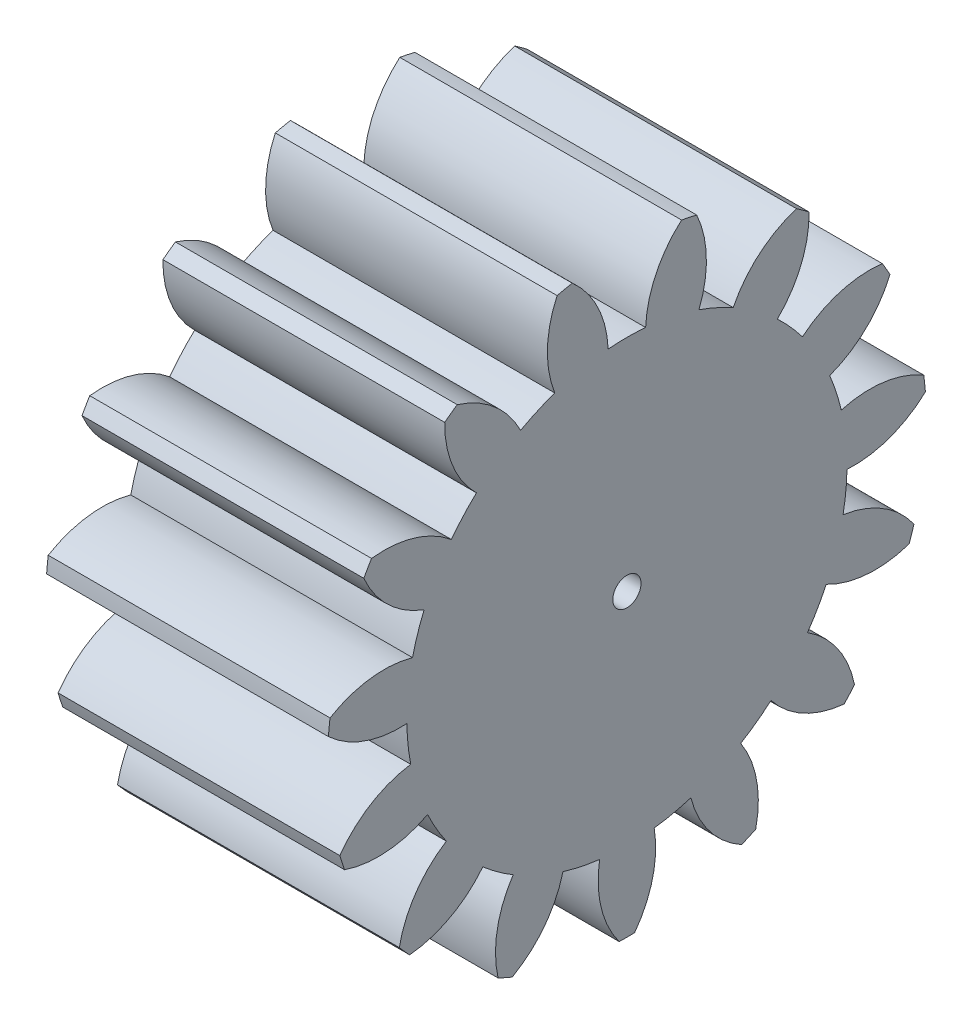
SolidWorks part; units mm, degrees
ref_plane "Plane1" through (0, 0, 0) normal (0, 0, 1) x (1, 0, 0)
ref_plane "Plane2" through (0, 0, 0) normal (0, 1, 0) x (1, 0, 0)
ref_plane "Plane3" through (0, 0, 0) normal (1, 0, 0) x (0, 0, -1)
other "Configuration Table"
sketch "HoldingSke" plane through (0, 0, 0) normal (0, 1, 0) x (1, 0, 0)
  line L0 (0, 0) -> (0.9659, -0.2588)
  line L1 (-15, 0) -> (100, 0) construction
  line L2 (0, 0) -> (-2.1039, 2.3779)
  line L3 (0, 0) -> (-11.863, 4.5341)
  line L4 (0, 0) -> (8.3417, 2.2352)
  line L5 (0, 0) -> (-46.8476, -17.4728)
  line L6 (0, 0) -> (-6.6317, -4.4744)
  line L7 (-2.1039, 2.3779) -> (8.6586, 51.2059)
  line L8 (-76.2, 54.61) -> (-76.1, 54.61)
  line L9 (-71.009, 38.7566) -> (-53.1078, 45.2721)
  line L10 (-76.2, 71.12) -> (104.1128, 71.12)
  line L11 (0, 0) -> (-8, 0)
  line L12 (-76.2, 101.6) -> (-76.162, 101.6)
  line L13 (24.9733, 27.94) -> (52.9518, 28.4284)
  line L14 (24.9733, 27.94) -> (24.9743, 27.94)
  line L15 (24.9733, 27.94) -> (100.4006, 29.5858)
  line L16 (-63.627, -1) -> (-12.827, -1)
  circle A0 centre (0, 0) radius 0.4
  circle A1 centre (0, 0) radius 6.249
  circle A2 centre (0, 0) radius 37.5
  circle A3 centre (0, 0) radius 0.4
  dimension "MHD" = 12.498
  dimension "Hub_dia" = 75
  dimension "Bore" = 0.8
  dimension "MBD" = 0.8
  dimension "Num_teeth" = 15
  dimension "Pitch" = 1
  dimension "Overall_len" = 50
  dimension "Show_teeth" = 15
  dimension "Thickness" = 8
  dimension "OAL" = 50.0001
  dimension "T_dim" = 0.1
  dimension "Ap" = 20
  dimension "H" = 19.05
  dimension "Pitch_radius" = 180.3128
  dimension "Width" = 8
  dimension "Backlash" = 0.038
  dimension "Addendum_fac" = 1
  dimension "Dedendum_fac" = 1.25
  dimension "Clearance_fac" = 0.25
  dimension "Dedendum_add" = 0.001
  dimension "Module" = 1
sketch "BasProSke" plane through (0, 0, 0) normal (0, 1, 0) x (1, 0, 0)
  line L0 (-10, 0) -> (60, 0) construction
  line L1 (0, 0) -> (0, 8.5)
  line L2 (0, 0) -> (8, 0)
  line L3 (8, 0) -> (8, 8.5)
  line L4 (8, 8.5) -> (0, 8.5)
  dimension "Thickness" = 8
  dimension "Diameter" = 17
revolve "Base-Revolve" add sketch "BasProSke" angle 360 about L0
sketch "TooCutSke" plane through (0, 0, 0) normal (1, 0, 0) x (0, 0, -1)
  line L1 (0, 0) -> (0, 107) construction
  line L2 (0, 0) -> (-0.8504, 7.4516) construction
  line L3 (0, 0) -> (-3.1044, 14.6049) construction
  line L4 (-0.8504, 7.4516) -> (-1.5522, 7.3025) construction
  arc A0 (0.5316, 6.2263) -> (-0.5316, 6.2263) centre (0, 0) ccw
  arc A1 (1.5766, 8.3784) -> (-1.5766, 8.3784) centre (0, 0) ccw
  circle A2 centre (0, 0) radius 7.5 construction
  circle A3 centre (0, 0) radius 7.0477 construction
  arc A4 (-0.5316, 6.2263) -> (-1.5766, 8.3784) centre (-3.5289, 6.1005) ccw
  arc A5 (1.5766, 8.3784) -> (0.5316, 6.2263) centre (3.5289, 6.1005) ccw
  dimension "Root_dia" = 12.498
  dimension "Overcut_dia" = 17.0508
  dimension "Pitch_dia" = 15
  dimension "Base_dia" = 14.0954
  dimension "Flank_rad" = 3
  dimension "Half_ang" = 12
  dimension "Half_CT" = 0.7175
extrude "ToothCut" cut sketch "TooCutSke" along normal through all
fillet "Breaks" [suppressed] radius 0.02
fillet "RootFillets" [suppressed] radius 0.251
pattern_circular "TeethCuts" count 15 every 24 about axis through (-10, 0, 0) along (1, 0, 0) of "ToothCut", "RootFillets", "Breaks"
sketch "HubNeaOneSke" plane through (0, 0, 0) normal (-1, 0, 0) x (0, 0, 1)
  circle A0 centre (0, 0) radius 6.249
  dimension "Diameter" = 12.498
extrude "HubNearOne" [suppressed] add sketch "HubNeaOneSke" along normal blind 42.0001
sketch "HubNeaBotSke" plane through (0, 0, 0) normal (-1, 0, 0) x (0, 0, 1)
  circle A0 centre (0, 0) radius 6.249
  dimension "Diameter" = 12.498
extrude "HubNearBoth" [suppressed] add sketch "HubNeaBotSke" along normal blind 21
ref_plane "FarPln" through (8, 0, 0) normal (1, 0, 0) x (0, 0, -1)
sketch "HubFarSke" plane through (8, 0, 0) normal (1, 0, 0) x (0, 0, -1)
  circle A0 centre (0, 0) radius 6.249
  dimension "Diameter" = 12.498
extrude "HubFar" [suppressed] add sketch "HubFarSke" along normal blind 21
sketch "BorSke" plane through (0, 0, 0) normal (1, 0, 0) x (0, 0, -1)
  circle A0 centre (0, 0) radius 0.4
  dimension "Diameter" = 0.8
extrude "Bore" cut sketch "BorSke" along normal mid plane 100.0001
sketch "KeySke" plane through (0, 0, 0) normal (1, 0, 0) x (0, 0, -1)
  line L0 (-0.05, 0) -> (-0.05, 0.5)
  line L1 (-0.05, 0.5) -> (0.05, 0.5)
  line L2 (0.05, 0.5) -> (0.05, 0)
  line L3 (0, 0) -> (0, 34) construction
  line L4 (-0.05, 0) -> (0.05, 0)
  dimension "Offset" = 0.5
  dimension "Width" = 0.1
extrude "Keyway" [suppressed] cut sketch "KeySke" along normal mid plane 100.0001
pattern_circular "Keyway2" [suppressed] count 2 every 90 about axis through (-10, 0, 0) along (1, 0, 0)
equation "' \"Module@HoldingSke\" = 6.35"
equation "' \"Num_teeth@HoldingSke\" = 12"
equation "' \"Ap@HoldingSke\" =  20"
equation "' \"Ap@HoldingSke\" = 20"
equation "' \"Width@HoldingSke\" = 0.5 * 25.4"
equation "' \"Hub_dia@HoldingSke\"= 1 * 25.4"
equation "' \"Hub_dia@HoldingSke\" = 1 * 25.4"
equation "' \"Overall_len@HoldingSke\" = 1.0 * 25.4"
equation "' \"Bore@HoldingSke\" = 0.75 * 25.4"
equation "' \"T_dim@HoldingSke\" = 0.1 * 25.4"
equation "' \"Width@KeySke\" = 0.25 * 25.4"
equation "' \"Show_teeth@HoldingSke\" = 13"
equation "' \"Backlash@HoldingSke\" = 0.009 * 25.4"
equation "' \"Addendum_fac@HoldingSke\" = 1.0"
equation "' \"Dedendum_fac@HoldingSke\" = 1.25"
equation "' \"Dedendum_add@HoldingSke\" = 0.00005 * 25.4"
equation "' \"Clearance_fac@HoldingSke\" = 0.25"
equation "\"Pitch@HoldingSke\" = 1 / \"Module@HoldingSke\""
equation "\"Overcut_dia@TooCutSke\" = (\"Num_teeth@HoldingSke\" + 2 * \"Addendum_fac@HoldingSke\") / \"Pitch@HoldingSke\" + 0.002 * 25.4"
equation "\"Pitch_dia@TooCutSke\" = \"Num_teeth@HoldingSke\" / \"Pitch@HoldingSke\""
equation "\"Base_dia@TooCutSke\" = \"Num_teeth@HoldingSke\" / \"Pitch@HoldingSke\" * cos((\"Ap@HoldingSke\"  * 3.14159265 / 180))"
equation "\"Root_dia@TooCutSke\" = (\"Num_teeth@HoldingSke\" + 2) / \"Pitch@HoldingSke\" - 2 * (\"Addendum_fac@HoldingSke\" + \"Dedendum_fac@HoldingSke\") / \"Pitch@HoldingSke\" - \"Dedendum_add@HoldingSke\" * 2"
equation "\"Half_ang@TooCutSke\" = 180 / \"Num_teeth@HoldingSke\""
equation "\"Half_CT@TooCutSke\" = \"Num_teeth@HoldingSke\" / \"Pitch@HoldingSke\" * sin((3.14159265 / 2 / \"Num_teeth@HoldingSke\")) / 2 - 7 * \"Backlash@HoldingSke\" / 4"
equation "\"Flank_rad@TooCutSke\" = \"Num_teeth@HoldingSke\" / \"Pitch@HoldingSke\" / 5"
equation "\"Radius@RootFillets\" = \"Clearance_fac@HoldingSke\" / \"Pitch@HoldingSke\" + \"Dedendum_add@HoldingSke\""
equation "\"Break_rad@Breaks\" = 0.02 / \"Pitch@HoldingSke\""
equation "\"Thickness@HoldingSke\" = \"Width@HoldingSke\""
equation "\"OAL@HoldingSke\" = \"Thickness@HoldingSke\""
equation "\"MHD@HoldingSke\" = (\"Num_teeth@HoldingSke\" + 2) / \"Pitch@HoldingSke\" - 2 * (\"Addendum_fac@HoldingSke\" + \"Dedendum_fac@HoldingSke\")  / \"Pitch@HoldingSke\" - \"Dedendum_add@HoldingSke\" * 2"
equation "\"MBD@HoldingSke\" = (\"Num_teeth@HoldingSke\" + 2) / \"Pitch@HoldingSke\" - 2 * (\"Addendum_fac@HoldingSke\" + \"Dedendum_fac@HoldingSke\")  / \"Pitch@HoldingSke\" - \"Dedendum_add@HoldingSke\" * 2 - 0.002 * 25.4"
equation "\"MHD@HoldingSke\" = ((sgn( \"MHD@HoldingSke\" - \"Hub_dia@HoldingSke\" )-1)*( \"MHD@HoldingSke\" - \"Hub_dia@HoldingSke\" ))/-2+ \"Hub_dia@HoldingSke\""
equation "\"MBD@HoldingSke\" = ((sgn( \"MBD@HoldingSke\" - \"Bore@HoldingSke\" )-1)*( \"MBD@HoldingSke\" - \"Bore@HoldingSke\" ))/-2+ \"Bore@HoldingSke\""
equation "\"OAL@HoldingSke\" = ((sgn( \"OAL@HoldingSke\" - \"Overall_len@HoldingSke\" )+1)*( \"OAL@HoldingSke\" - \"Overall_len@HoldingSke\" ))/2 + \"Overall_len@HoldingSke\" + 0.000002 * 25.4"
equation "\"Num_teeth@TeethCuts\" = int( \"Show_teeth@HoldingSke\" ) + 1"
equation "\"Num_teeth@TeethCuts\" = ((sgn( \"Num_teeth@TeethCuts\" - \"Num_teeth@HoldingSke\" )-1)*( \"Num_teeth@TeethCuts\" - \"Num_teeth@HoldingSke\" ))/-2+ \"Num_teeth@HoldingSke\""
equation "\"Num_teeth@TeethCuts\" = ((sgn( \"Num_teeth@TeethCuts\" - 2.0)+1)*( \"Num_teeth@TeethCuts\" - 2.0))/2 +2.0"
equation "\"Angle@TeethCuts\" = 360.0 / \"Num_teeth@HoldingSke\""
equation "\"Diameter@BasProSke\" = (\"Num_teeth@HoldingSke\" + 2 * \"Addendum_fac@HoldingSke\") / \"Pitch@HoldingSke\""
equation "\"Thickness@BasProSke\"  = \"Thickness@HoldingSke\""
equation "' \"Fillet_rad@BasProSke\" =  \"Thickness@HoldingSke\" * 0.05"
equation "' \"Fillet_rad@BasProSke\" = \"Thickness@HoldingSke\" * 0.05"
equation "\"MHD@HoldingSke\" = ((sgn( \"MHD@HoldingSke\" - \"Root_dia@TooCutSke\" )-1)*( \"MHD@HoldingSke\" - \"Root_dia@TooCutSke\" ))/-2+ \"Root_dia@TooCutSke\""
equation "\"Diameter@HubNeaOneSke\" = \"MHD@HoldingSke\""
equation "\"Length@HubNearOne\" = \"OAL@HoldingSke\" - \"Thickness@BasProSke\""
equation "\"Diameter@HubNeaBotSke\" = \"MHD@HoldingSke\""
equation "\"Length@HubNearBoth\" = ( \"OAL@HoldingSke\" - \"Thickness@BasProSke\" ) / 2.0"
equation "\"Thickness@FarPln\" = \"Thickness@BasProSke\""
equation "\"Diameter@HubFarSke\" = \"MHD@HoldingSke\""
equation "\"Length@HubFar\" = ( \"OAL@HoldingSke\" - \"Thickness@BasProSke\" ) / 2.0"
equation "\"Diameter@BorSke\" = \"MBD@HoldingSke\""
equation "\"D1@Bore\" = \"OAL@HoldingSke\" * 2.0"
equation "\"D1@Keyway\" = \"OAL@HoldingSke\" * 2.0"
equation "\"Offset@KeySke\" = \"T_dim@HoldingSke\" + \"MBD@HoldingSke\" / 2.0"
